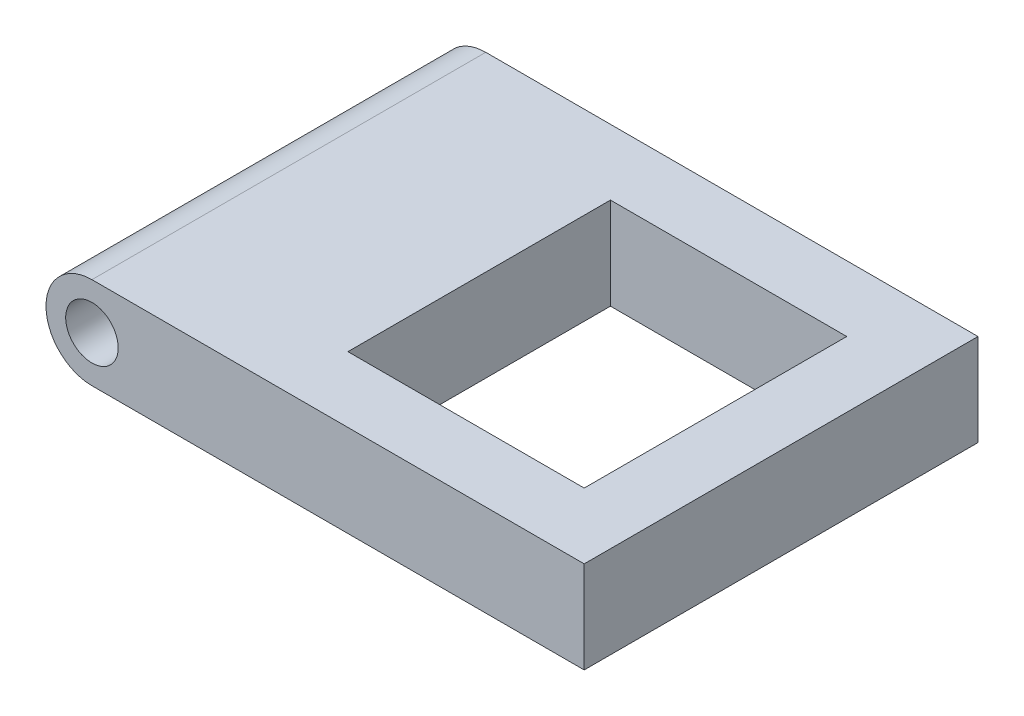
SolidWorks part; units mm, degrees
ref_plane "前视基准面" through (0, 0, 0) normal (0, 0, 1) x (1, 0, 0)
ref_plane "上视基准面" through (0, 0, 0) normal (0, 1, 0) x (1, 0, 0)
ref_plane "右视基准面" through (0, 0, 0) normal (1, 0, 0) x (0, 0, -1)
other "Configuration Table"
sketch "草图1" plane through (0, 0, 0) normal (0, 1, 0) x (1, 0, 0)
  line L0 (0, 0) -> (55, 0)
  line L1 (55, 0) -> (55, 60)
  line L2 (55, 60) -> (0, 60)
  line L3 (0, 60) -> (0, 0)
  line L4 (9, 10) -> (45, 10)
  line L5 (45, 10) -> (45, 50)
  line L6 (45, 50) -> (9, 50)
  line L7 (9, 50) -> (9, 10)
  point P5 (9, 10)
extrude "凸台-拉伸1" add sketch "草图1" along normal blind 14
sketch "草图2" plane through (0, 0, 0) normal (0, 0, 1) x (1, 0, 0)
  line L0 (0, 0) -> (-20, 0)
  line L2 (-20, 14) -> (0, 14)
  line L3 (0, 14) -> (0, 0)
  arc A0 (-20, 14) -> (-20, 0) centre (-20, 7) ccw
  circle A1 centre (-20, 7) radius 4
extrude "凸台-拉伸2" add sketch "草图2" against normal blind 60
